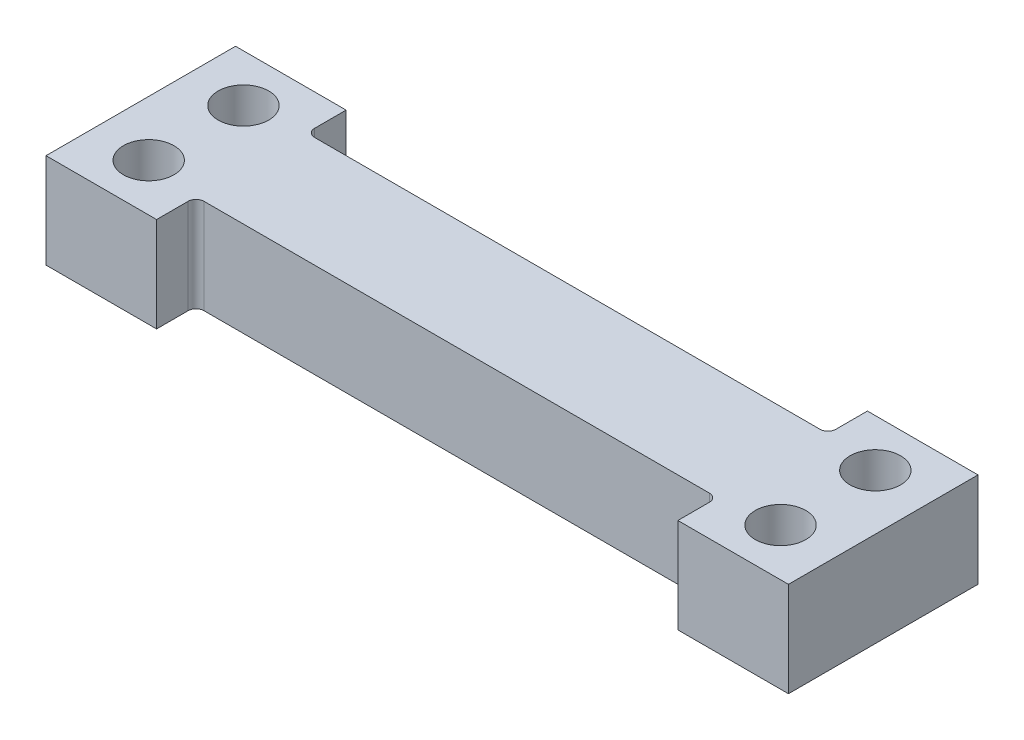
SolidWorks part; units mm, degrees
ref_plane "Front Plane" through (0, 0, 0) normal (0, 0, 1) x (1, 0, 0)
ref_plane "Top Plane" through (0, 0, 0) normal (0, 1, 0) x (1, 0, 0)
ref_plane "Right Plane" through (0, 0, 0) normal (1, 0, 0) x (0, 0, -1)
sketch "Sketch1" plane through (0, 0, 0) normal (0, 1, 0) x (1, 0, 0)
  line L0 (0, 0) -> (0, 12)
  line L1 (0, 12) -> (7, 12)
  line L2 (7, 12) -> (7, 9.5)
  line L3 (7, 9.5) -> (40, 9.5)
  line L4 (40, 9.5) -> (40, 12)
  line L5 (40, 12) -> (47, 12)
  line L6 (47, 12) -> (47, 0)
  line L7 (47, 0) -> (40, 0)
  line L8 (40, 0) -> (40, 2.5)
  line L9 (40, 2.5) -> (7, 2.5)
  line L10 (7, 2.5) -> (7, 0)
  line L11 (7, 0) -> (0, 0)
  line L12 (3.5, 12) -> (3.5, 0) construction
  line L13 (3.5, 9) -> (3.5, 3) construction
  line L14 (23.5, 9.5) -> (23.5, 2.5) construction
  circle A0 centre (3.5, 9) radius 1.6
  circle A1 centre (3.5, 3) radius 1.6
  circle A2 centre (43.5, 3) radius 1.6
  circle A3 centre (43.5, 9) radius 1.6
  point P19 (3.5, 6)
  point P20 (0, 6)
  point P23 (3.5, 6)
  dimension "D5" = 3.2
  dimension "D1" = 7
  dimension "D2" = 12
  dimension "D3" = 47
  dimension "D4" = 7
  dimension "D6" = 6
extrude "Boss-Extrude1" add sketch "Sketch1" along normal blind 6
fillet "Fillet1" radius 0.5 4 edges at (7, 3, -9.5) (40, 3, -9.5) (40, 3, -2.5) (7, 3, -2.5)
